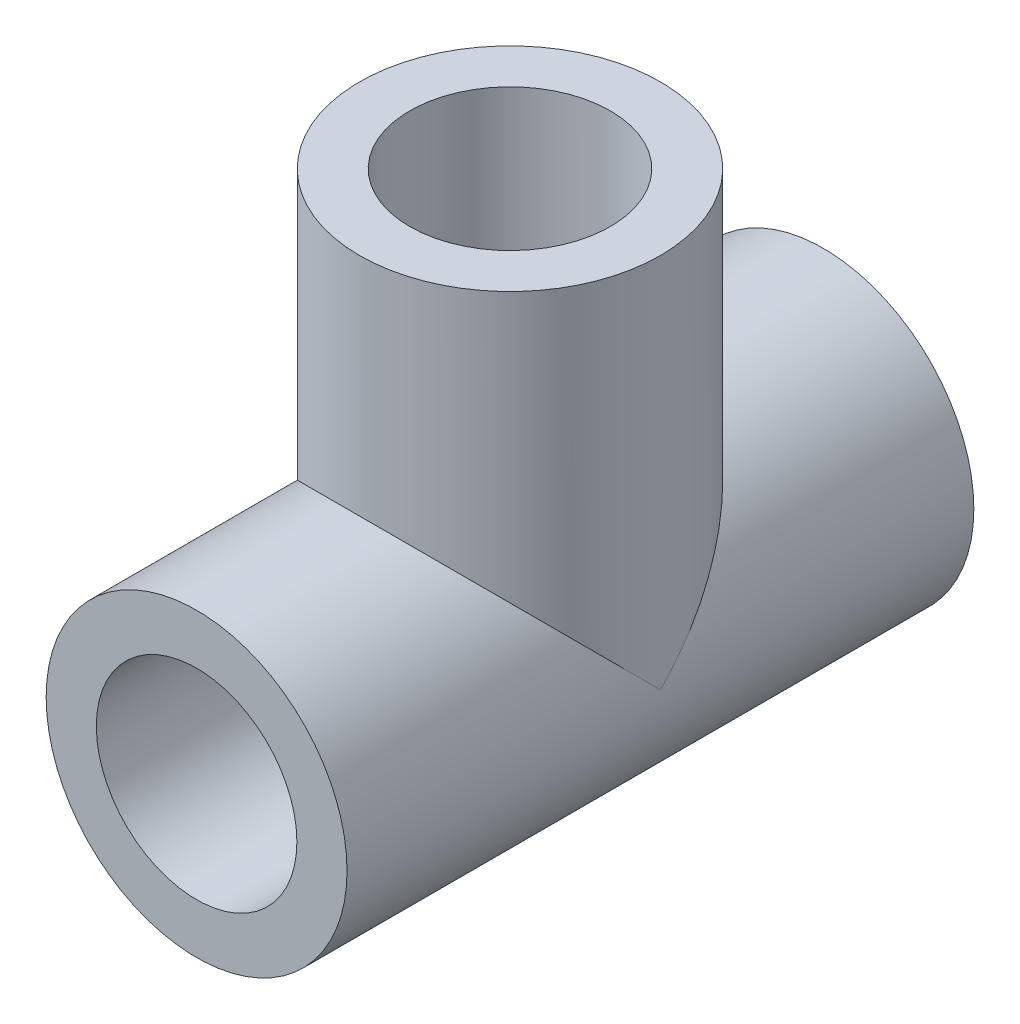
SolidWorks part; units mm, degrees
material "ABS"
ref_plane "Front Plane" through (0, 0, 0) normal (0, 0, 1) x (1, 0, 0)
ref_plane "Top Plane" through (0, 0, 0) normal (0, 1, 0) x (1, 0, 0)
ref_plane "Right Plane" through (0, 0, 0) normal (1, 0, 0) x (0, 0, -1)
sketch "Sketch1" plane through (0, 0, 0) normal (0, 0, 1) x (1, 0, 0)
  circle A0 centre (0, 0) radius 6
  circle A3 centre (0, 0) radius 4
  dimension "D1" = 12
  dimension "D2" = 8
extrude "Boss-Extrude1" add sketch "Sketch1" along normal mid plane 25
sketch "Sketch2" plane through (0, 0, 0) normal (0, 1, 0) x (1, 0, 0)
  circle A0 centre (0, 0) radius 4
  circle A2 centre (0, 0) radius 6
  dimension "D1" = 8
  dimension "D2" = 2
extrude "Boss-Extrude2" add sketch "Sketch2" along normal blind 15
sketch "Sketch3" plane through (0, 0, 12.5) normal (0, 0, 1) x (1, 0, 0)
  circle A0 centre (0, 0) radius 4 construction
  circle A1 centre (0, 0) radius 4
extrude "Cut-Extrude1" cut sketch "Sketch3" against normal blind 25
